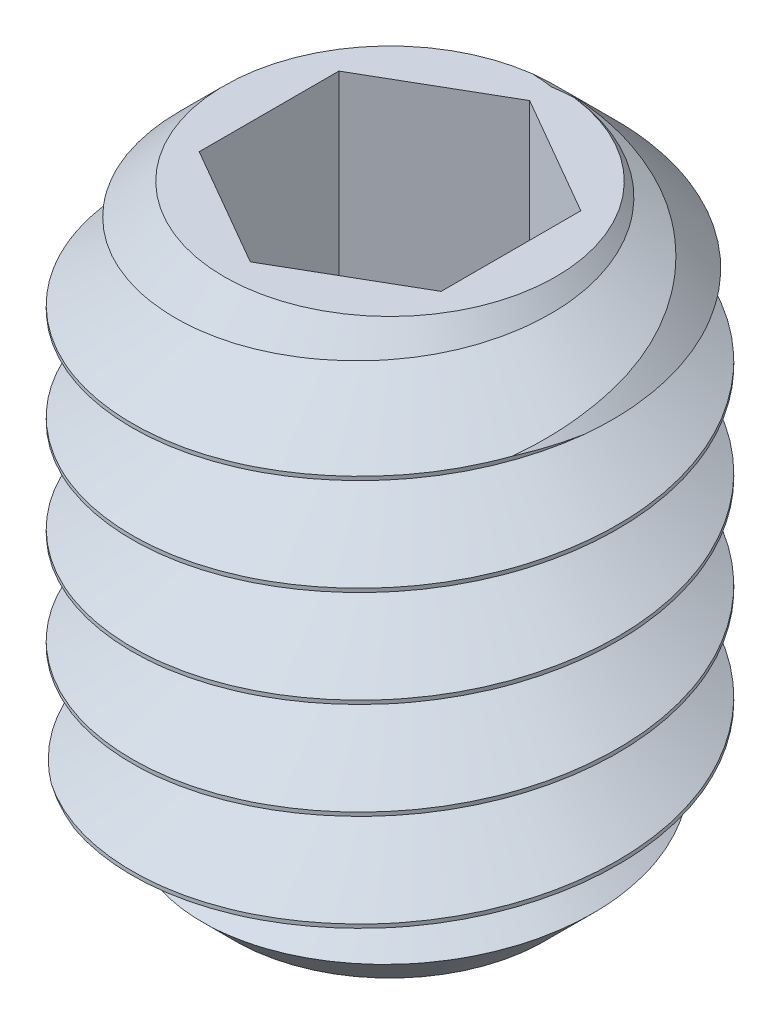
SolidWorks part; units mm, degrees
material "Alloy Steel"
ref_plane "Front Plane" through (0, 0, 0) normal (0, 0, 1) x (1, 0, 0)
ref_plane "Top Plane" through (0, 0, 0) normal (0, 1, 0) x (1, 0, 0)
ref_plane "Right Plane" through (0, 0, 0) normal (1, 0, 0) x (0, 0, -1)
sketch "Sketch1" plane through (0, 0, 0) normal (0, 0, 1) x (1, 0, 0)
  line L0 (0, 0) -> (0, 54.6222) construction
  line L1 (0, 0.5866) -> (-1.016, 0)
  line L2 (-1.016, 0) -> (-1.27, 0)
  line L3 (-1.27, 0) -> (-1.9939, 0.7239)
  line L4 (-1.9939, 0.7239) -> (-1.9939, 4.1275)
  line L5 (-1.9939, 4.1275) -> (-1.3589, 4.7625)
  line L6 (-1.3589, 4.7625) -> (0, 4.7625)
  line L7 (0, 4.7625) -> (0, 0.5866)
  dimension "D1" = 60
  dimension "D2" = 2.032
  dimension "D3" = 135
  dimension "D4" = 135
  dimension "D5" = 0.635
  dimension "D6" = 3.9878
  dimension "D7" = 0.254
  dimension "D8" = 4.7625
revolve "Revolve1" add sketch "Sketch1" angle 360 about L0
sketch "Sketch2" plane through (0, 4.7625, 0) normal (0, 1, 0) x (1, 0, 0)
  line L0 (0, 0) -> (0, 1.3178) construction
  line L1 (0, 1.1457) -> (-0.9922, 0.5728)
  line L2 (-0.9922, 0.5728) -> (-0.9922, -0.5728)
  line L3 (-0.9922, -0.5728) -> (0, -1.1457)
  line L4 (0, -1.1457) -> (0.9922, -0.5728)
  line L5 (0.9922, -0.5728) -> (0.9922, 0.5728)
  line L6 (0.9922, 0.5728) -> (0, 1.1457)
  circle A0 centre (0, 0) radius 0.9922 construction
  dimension "D1" = 1.9844
extrude "Cut-Extrude1" cut sketch "Sketch2" against normal blind 1.778
sketch "Sketch3" plane through (0, 4.7625, 0) normal (0, 1, 0) x (1, 0, 0)
  circle A0 centre (0, 0) radius 1.9939 construction
  circle A1 centre (0, 0) radius 1.9939
curve "Helix/Spiral1" pitch 0.795 height 9.525 turns 11.9808
sketch "Sketch4" plane through (0, 0, 0) normal (1, 0, 0) x (0, 0, -1)
  line L0 (-2.0193, 5.5562) -> (-2.0193, 4.7625)
  line L1 (-2.0193, 4.7625) -> (-1.3319, 5.1594)
  line L2 (-1.3319, 5.1594) -> (-2.0193, 5.5562)
  line L3 (-1.3319, 5.1594) -> (-2.0193, 5.1594) construction
  line L5 (-2.0193, 5.5562) -> (-1.3319, 5.9531) construction
  line L6 (-1.3319, 5.9531) -> (-2.0193, 6.35) construction
  line L7 (-2.0193, 6.35) -> (-2.0193, 5.5562) construction
  line L8 (1.3589, 4.7625) -> (-1.3589, 4.7625) construction
  line L10 (0, 4.7625) -> (0, 10.7636) construction
  dimension "D1" = 60
  dimension "D2" = 0.7937
  dimension "D3" = 4.0386
sweep "Cut-Sweep3" cut profiles "Sketch4" path "Helix/Spiral1"
